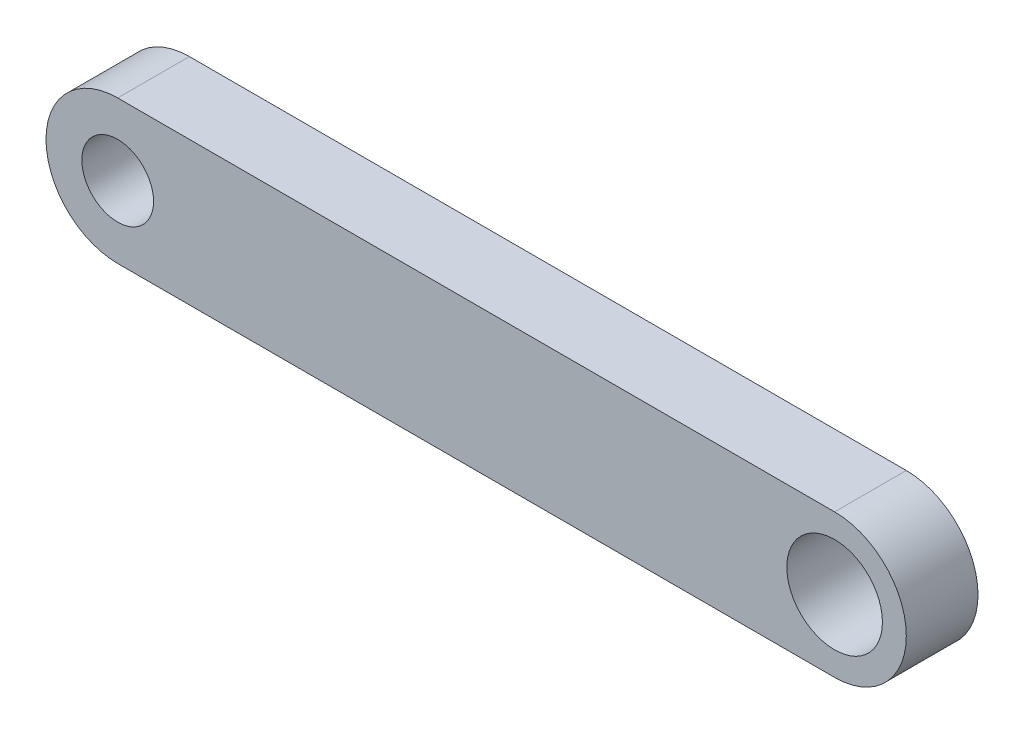
SolidWorks part; units mm, degrees
ref_plane "前视基准面" through (0, 0, 0) normal (0, 0, 1) x (1, 0, 0)
ref_plane "上视基准面" through (0, 0, 0) normal (0, 1, 0) x (1, 0, 0)
ref_plane "右视基准面" through (0, 0, 0) normal (1, 0, 0) x (0, 0, -1)
sketch "草图1" plane through (0, 0, 0) normal (0, 0, 1) x (1, 0, 0)
  line L0 (-80.4405, 0) -> (219.5595, 0) construction
  line L1 (-80.4405, 30) -> (219.5595, 30)
  line L2 (-80.4405, -30) -> (219.5595, -30)
  arc A0 (-80.4405, 30) -> (-80.4405, -30) centre (-80.4405, 0) ccw
  arc A1 (219.5595, -30) -> (219.5595, 30) centre (219.5595, 0) ccw
  circle A2 centre (-80.4405, 0) radius 15
  circle A3 centre (219.5595, 0) radius 20
  point P3 (69.5595, 0)
  dimension "D1" = 300
  dimension "D2" = 30
  dimension "D3" = 30
  dimension "D4" = 40
extrude "凸台-拉伸1" add sketch "草图1" along normal blind 30
